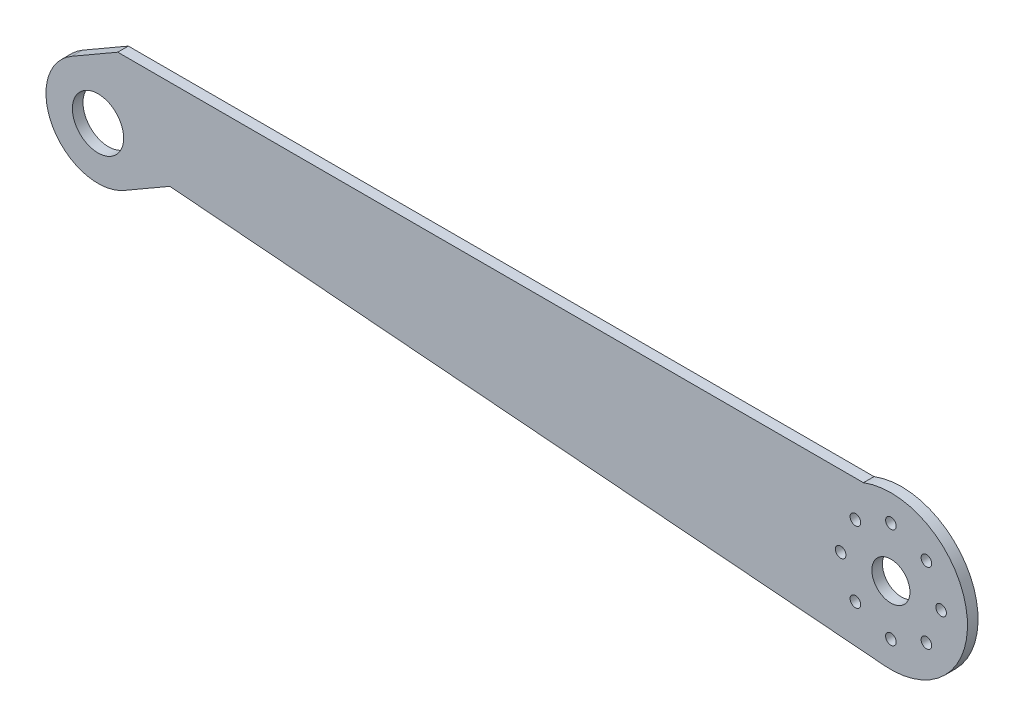
SolidWorks part; units mm, degrees
ref_plane "前视基准面" through (0, 0, 0) normal (0, 0, 1) x (1, 0, 0)
ref_plane "上视基准面" through (0, 0, 0) normal (0, 1, 0) x (1, 0, 0)
ref_plane "右视基准面" through (0, 0, 0) normal (1, 0, 0) x (0, 0, -1)
sketch "草图1" plane through (0, 0, 0) normal (0, 0, 1) x (1, 0, 0)
  line L0 (0, 0) -> (300, 0) construction
  line L1 (0, 0) -> (-15.3092, 26.5163) construction
  line L6 (-9.85, 17.0607) -> (7.4705, 27.0607)
  line L7 (9.85, -17.0607) -> (27.1705, -7.0607)
  line L8 (300, 0) -> (350.6731, 87.7683) construction
  line L9 (27.1705, -7.0607) -> (297.6656, -28.9059)
  line L11 (289.6247, 27.0607) -> (7.4705, 27.0607)
  circle A0 centre (0, 0) radius 9.7
  circle A1 centre (300, 0) radius 19 construction
  circle A2 centre (300, 0) radius 7.2
  circle A3 centre (319, 0) radius 2
  circle A18 centre (313.435, -13.435) radius 2
  circle A19 centre (300, -19) radius 2
  circle A20 centre (286.565, -13.435) radius 2
  circle A21 centre (281, 0) radius 2
  circle A22 centre (286.565, 13.435) radius 2
  circle A23 centre (300, 19) radius 2
  circle A24 centre (313.435, 13.435) radius 2
  circle A25 centre (0, 0) radius 19.7 construction
  arc A26 (9.85, -17.0607) -> (-9.85, 17.0607) centre (0, 0) cw
  circle A27 centre (300, 0) radius 29 construction
  arc A28 (289.6247, 27.0607) -> (297.6656, -28.9059) centre (299.9992, -0.0097) cw
  dimension "D1" = 19.4
  dimension "D3" = 38
  dimension "D4" = 14.4
  dimension "D5" = 4
  dimension "D6" = 8
  dimension "D7" = 10
  dimension "D10" = 10
  dimension "D2" = 300
  dimension "D8" = 120
  dimension "D9" = 20
  dimension "D11" = 120
extrude "凸台-拉伸1" add sketch "草图1" along normal blind 4
